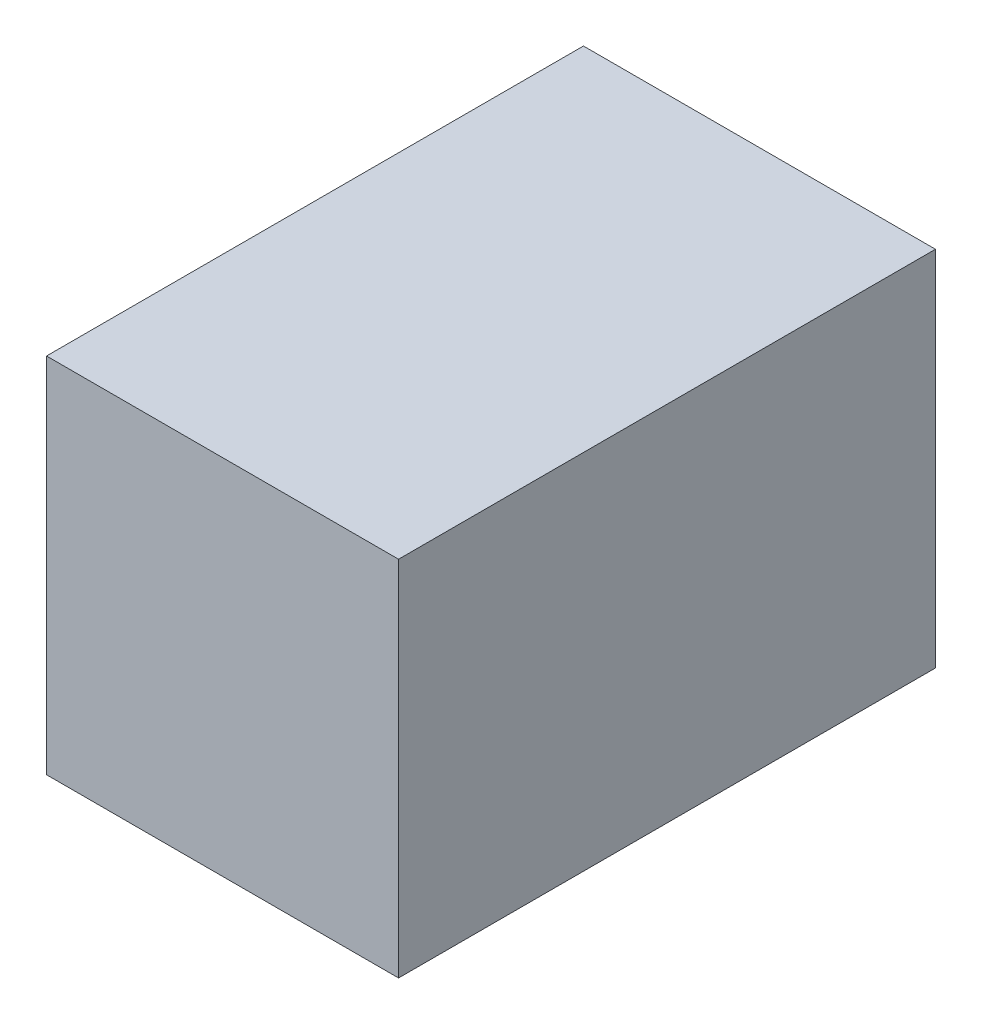
SolidWorks part; units mm, degrees
material "Copper"
ref_plane "Front Plane" through (0, 0, 0) normal (0, 0, 1) x (1, 0, 0)
ref_plane "Top Plane" through (0, 0, 0) normal (0, 1, 0) x (1, 0, 0)
ref_plane "Right Plane" through (0, 0, 0) normal (1, 0, 0) x (0, 0, -1)
sketch "Sketch1" plane through (0, 0, 0) normal (0, 0, 1) x (1, 0, 0)
  line L1 (0, 0) -> (-99, 0)
  line L2 (0, 0) -> (0, -102)
  line L3 (0, -102) -> (-99, -102)
  line L4 (-99, 0) -> (-99, -102)
  dimension "D1" = 99
  dimension "D2" = 102
extrude "Boss-Extrude1" add sketch "Sketch1" along normal blind 151
